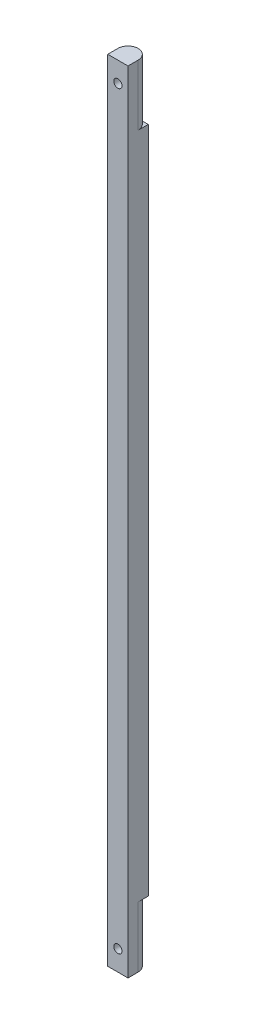
SolidWorks part; units mm, degrees
material "6061-T6 (SS)"
ref_plane "Front Plane" through (0, 0, 0) normal (0, 0, 1) x (1, 0, 0)
ref_plane "Top Plane" through (0, 0, 0) normal (0, 1, 0) x (1, 0, 0)
ref_plane "Right Plane" through (0, 0, 0) normal (1, 0, 0) x (0, 0, -1)
sketch "Sketch1" plane through (0, 0, 0) normal (0, 1, 0) x (1, 0, 0)
  line L0 (-3.175, 3.175) -> (-3.175, 0)
  line L1 (-3.175, 0) -> (3.175, 0)
  line L2 (3.175, 0) -> (3.175, 3.175)
  arc A0 (-3.175, 3.175) -> (3.175, 3.175) centre (0, 3.175) cw
  point P5 (0, 0)
  point P8 (0, 6.35)
  dimension "D2" = 3.175
  dimension "D1" = 6.35
  dimension "D3" = 6.35
extrude "Boss-Extrude1" add sketch "Sketch1" along normal mid plane 247.65
hole_wizard "#5-40 Tapped Hole1" positions "Sketch2" profile "Sketch3" tap size "#5-40" standard "ANSI Inch" end condition through all
sketch "Sketch2" plane through (0, 0, 0) normal (0, 0, 1) x (1, 0, 0)
  line L0 (-3.175, -123.825) -> (3.175, -123.825) construction
  point P2 (0, -117.475)
  dimension "D1" = 6.35
sketch "Sketch3" plane through (0, -117.475, 0) normal (1, 0, 0) x (0, -1, 0)
  line L0 (0, 0) -> (0, 6.35)
  line L1 (0, 6.35) -> (1.289, 6.35)
  line L2 (1.289, 6.35) -> (1.289, 0)
  line L5 (1.289, 0) -> (0, 0)
  line L11 (0, -6.35) -> (0, 107.95) construction
  dimension "Thru Tap Drill Dia." = 2.5781
  dimension "Thru Tap Drill Depth" = 6.35
cosmetic thread "Hole Thread1" parameters "D2"=3.175
mirror "Mirror1" about plane through (0, 0, 0) normal (0, 1, 0) of "#5-40 Tapped Hole1"
cosmetic thread "Hole Thread2" parameters "D2"=3.175
sketch "Sketch4" plane through (0, 123.825, 0) normal (0, 1, 0) x (1, 0, 0)
  line L0 (-3.175, 0) -> (3.175, 0) construction
  line L1 (3.175, 6.35) -> (-3.175, 6.35)
  line L2 (3.175, 6.35) -> (3.175, 0)
  line L3 (3.175, 0) -> (-3.175, 0)
  line L4 (-3.175, 6.35) -> (-3.175, 0)
  line L5 (3.175, 6.35) -> (-3.175, 0) construction
  line L6 (3.175, 0) -> (-3.175, 6.35) construction
  line L7 (-3.175, 3.175) -> (-3.175, 0) construction
  line L8 (3.175, 0) -> (3.175, 3.175) construction
  point P0 (0, 3.175)
extrude "Boss-Extrude2" add sketch "Sketch4" against normal offset from surface (209.55 mm away) 19.05 from offset 19.05 up to face at (0, -123.825, -2.3813) offset against normal yes
